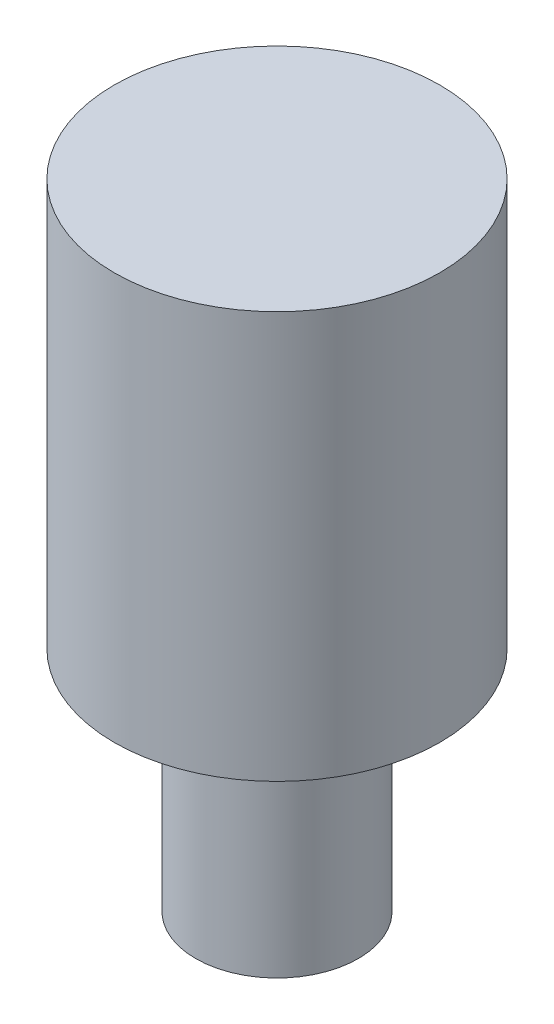
SolidWorks part; units mm, degrees
ref_plane "前基準面" through (0, 0, 0) normal (0, 0, 1) x (1, 0, 0)
ref_plane "上基準面" through (0, 0, 0) normal (0, 1, 0) x (1, 0, 0)
ref_plane "右基準面" through (0, 0, 0) normal (1, 0, 0) x (0, 0, -1)
sketch "草圖1" plane through (0, 0, 0) normal (0, 1, 0) x (1, 0, 0)
  circle A0 centre (0, 0) radius 1
  dimension "D1" = 2
extrude "填料-伸長1" add sketch "草圖1" along normal blind 2.8
sketch "草圖2" plane through (0, 2.8, 0) normal (0, 1, 0) x (1, 0, 0)
  circle A0 centre (0, 0) radius 2
  dimension "D1" = 4
extrude "填料-伸長2" add sketch "草圖2" along normal blind 5
